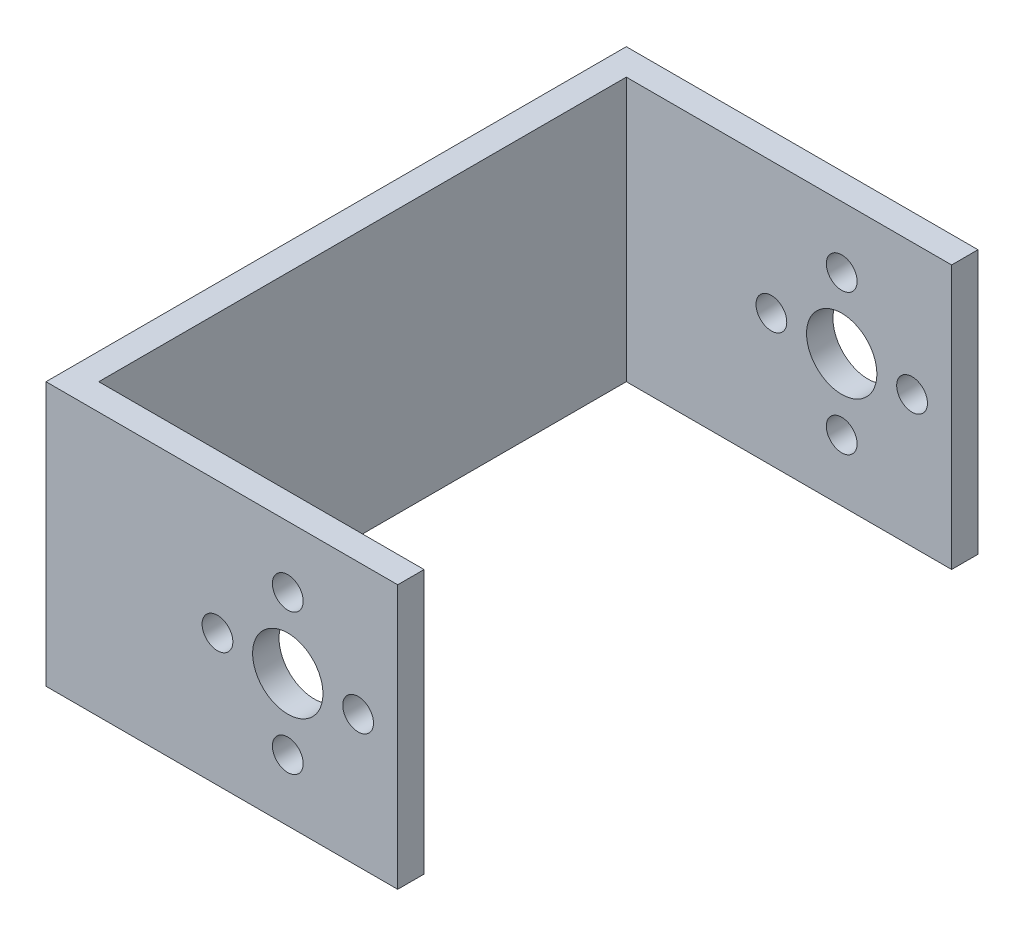
SolidWorks part; units mm, degrees
ref_plane "Front Plane" through (0, 0, 0) normal (0, 0, 1) x (1, 0, 0)
ref_plane "Top Plane" through (0, 0, 0) normal (0, 1, 0) x (1, 0, 0)
ref_plane "Right Plane" through (0, 0, 0) normal (1, 0, 0) x (0, 0, -1)
sketch "Sketch1" plane through (0, 0, 0) normal (0, 1, 0) x (1, 0, 0)
  line L0 (0, 0) -> (0, 66)
  line L2 (3, 63) -> (3, 3)
  line L3 (3, 3) -> (40, 3)
  line L4 (40, 3) -> (40, 0)
  line L5 (40, 0) -> (0, 0)
  line L6 (3, 63) -> (40, 63)
  line L7 (40, 63) -> (40, 66)
  line L8 (40, 66) -> (0, 66)
  point P8 (0, 64.601)
  point P11 (0, 73.0926)
  dimension "D1" = 3
  dimension "D2" = 3
  dimension "D3" = 37
  dimension "D4" = 60
  dimension "D5" = 3
extrude "Boss-Extrude1" add sketch "Sketch1" along normal blind 30
sketch "Sketch2" plane through (0, 0, 0) normal (0, 0, 1) x (1, 0, 0)
  line L0 (0, 15) -> (40, 15) construction
  line L1 (0, 30) -> (0, 0) construction
  line L2 (40, 30) -> (40, 0) construction
  circle A0 centre (27.5, 15) radius 4
  circle A1 centre (19.5, 15) radius 1.75
  circle A2 centre (27.5, 23) radius 1.75
  circle A3 centre (35.5, 15) radius 1.75
  circle A4 centre (27.5, 7) radius 1.75
  point P10 (27.2582, 15)
  point P19 (27.5, 15)
  dimension "D1" = 8
  dimension "D3" = 3.5
  dimension "D5" = 16
  dimension "D2" = 27.5
  dimension "D4" = 4
extrude "Cut-Extrude1" cut sketch "Sketch2" against normal through all
